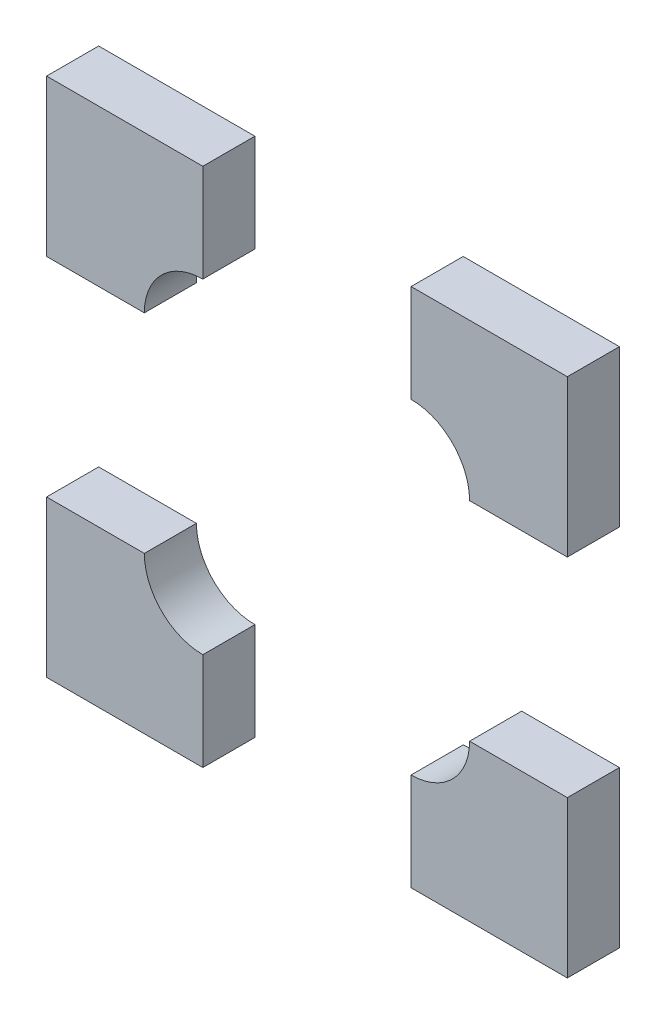
SolidWorks part; units mm, degrees
ref_plane "Front Plane" through (0, 0, 0) normal (0, 0, 1) x (1, 0, 0)
ref_plane "Top Plane" through (0, 0, 0) normal (0, 1, 0) x (1, 0, 0)
ref_plane "Right Plane" through (0, 0, 0) normal (1, 0, 0) x (0, 0, -1)
sketch "Sketch1" plane through (0, 0, 0) normal (0, 0, 1) x (1, 0, 0)
  line L1 (5, -5) -> (-5, -5)
  line L2 (5, -5) -> (5, 5)
  line L3 (5, 5) -> (-5, 5)
  line L4 (-5, -5) -> (-5, 5)
  line L5 (5, -5) -> (-5, 5) construction
  line L6 (5, 5) -> (-5, -5) construction
  line L7 (5, -2) -> (-5, -2)
  line L8 (5, -2) -> (5, 2)
  line L9 (5, 2) -> (-5, 2)
  line L10 (-5, -2) -> (-5, 2)
  line L11 (5, -2) -> (-5, 2) construction
  line L12 (5, 2) -> (-5, -2) construction
  line L13 (2, -5) -> (-2, -5)
  line L14 (2, -5) -> (2, 5)
  line L15 (2, 5) -> (-2, 5)
  line L16 (-2, -5) -> (-2, 5)
  line L17 (2, -5) -> (-2, 5) construction
  line L18 (2, 5) -> (-2, -5) construction
  circle A1 centre (-2, 2) radius 1.1232
  circle A2 centre (2, 2) radius 1.1232
  circle A3 centre (2, -2) radius 1.1232
  circle A4 centre (-2, -2) radius 1.1232
  point P0 (0, 0)
  dimension "D1" = 10
  dimension "D3" = 4
  dimension "D4" = 4
extrude "Boss-Extrude1" add sketch "Sketch1" along normal blind 1 contours A1 L16 L3 L4 L9 | A1 L7 L4 L1 L16 | A1 L14 L1 L2 L7 | A1 L9 L2 L3 L14
